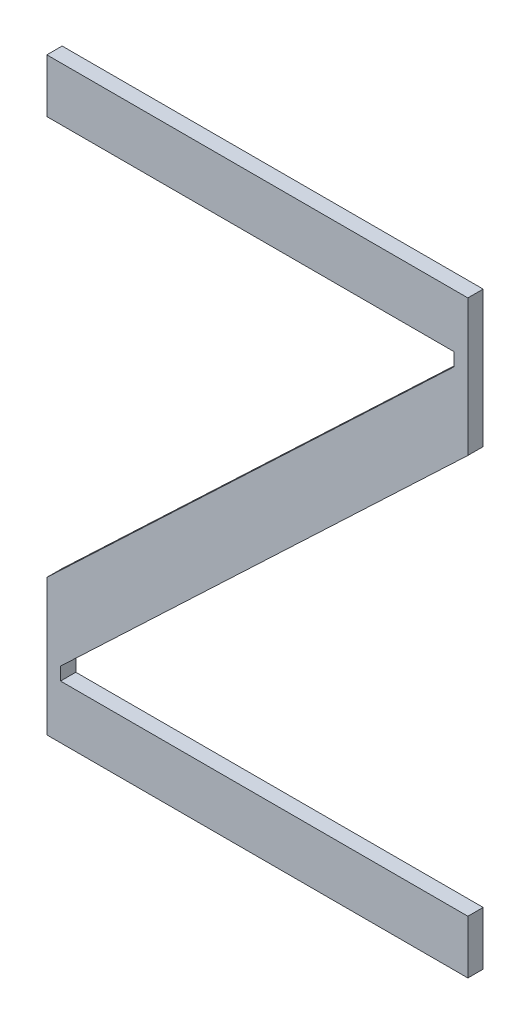
SolidWorks part; units mm, degrees
ref_plane "Front Plane" through (0, 0, 0) normal (0, 0, 1) x (1, 0, 0)
ref_plane "Top Plane" through (0, 0, 0) normal (0, 1, 0) x (1, 0, 0)
ref_plane "Right Plane" through (0, 0, 0) normal (1, 0, 0) x (0, 0, -1)
sketch "Sketch1" plane through (0, 0, 0) normal (0, 0, 1) x (1, 0, 0)
  line L0 (0, -70) -> (0, -178.5948)
  line L1 (0, 0) -> (-551, 0)
  line L2 (0, 0) -> (0, -70)
  line L3 (-18.2883, -70) -> (-551, -70)
  line L4 (-551, 0) -> (-551, -70)
  line L5 (-18.2883, -87.3325) -> (-551, -592.2052)
  line L6 (0, -178.5948) -> (-533.096, -683.8316)
  line L7 (-551, -592.2052) -> (-551, -700.8)
  line L8 (-18.2883, -70) -> (-18.2883, -87.3325)
  line L9 (-533.096, -700.8) -> (0, -700.8)
  line L10 (-551, -700.8) -> (-551, -770.8)
  line L11 (-551, -770.8) -> (0, -770.8)
  line L12 (0, -700.8) -> (0, -770.8)
  line L13 (-533.096, -683.8316) -> (-533.096, -700.8)
  dimension "D1" = 70
  dimension "D2" = 551
  dimension "D3" = 70
  dimension "D4" = 551
  dimension "D5" = 78.82
  dimension "D6" = 770.8
extrude "Boss-Extrude1" add sketch "Sketch1" along normal blind 20
